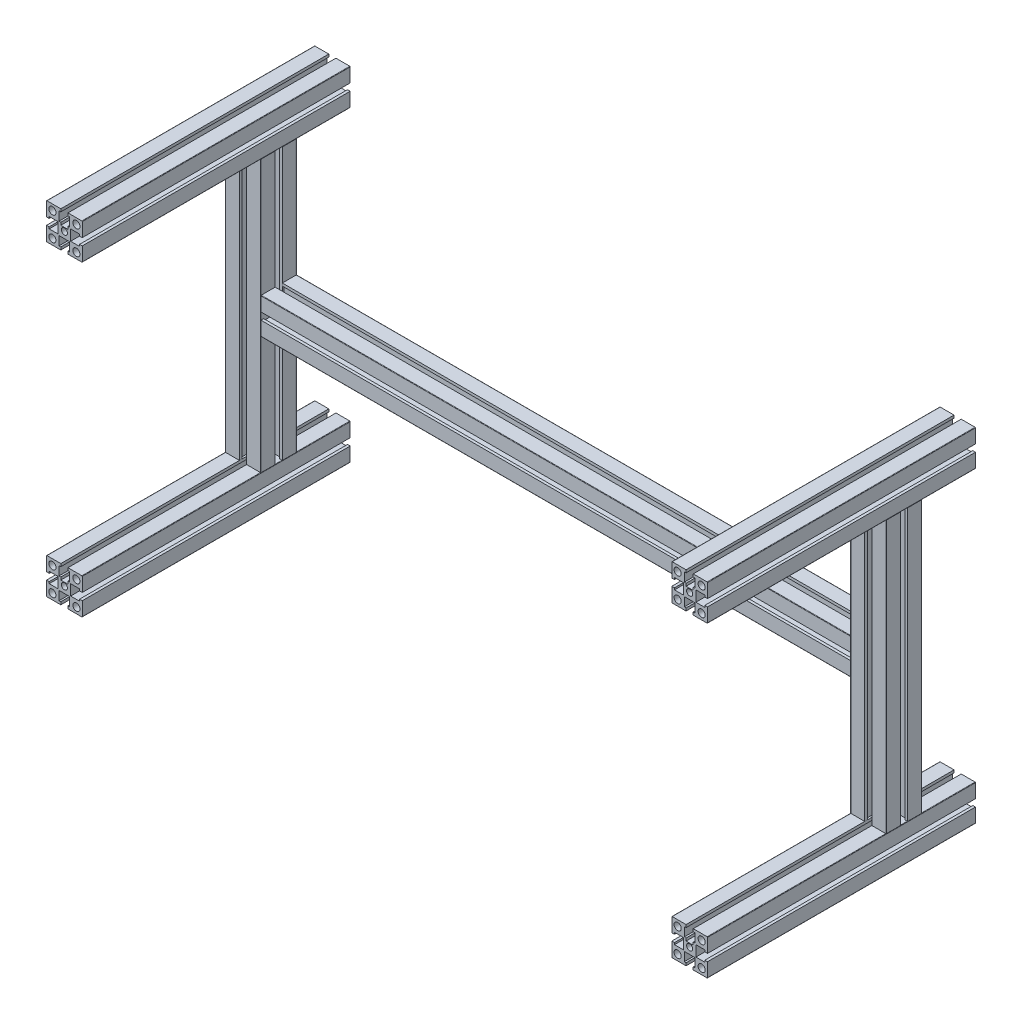
SolidWorks part; units mm, degrees
ref_plane "前视基准面" through (0, 0, 0) normal (0, 0, 1) x (1, 0, 0)
ref_plane "上视基准面" through (0, 0, 0) normal (0, 1, 0) x (1, 0, 0)
ref_plane "右视基准面" through (0, 0, 0) normal (1, 0, 0) x (0, 0, -1)
other "Configuration Table"
sketch3d "3D草图2"
  line L0 (-350, -172, 0) -> (-350, -172, 300)
  line L1 (-350, 172, 0) -> (350, 172, 0) construction
  line L2 (-350, 172, 0) -> (-350, -172, 0) construction
  line L3 (-350, -172, 0) -> (350, -172, 0) construction
  line L4 (350, 172, 0) -> (350, -172, 0) construction
  line L5 (-350, 172, 0) -> (350, -172, 0) construction
  line L6 (-350, -172, 0) -> (350, 172, 0) construction
  line L7 (350, -172, 0) -> (350, -172, 300)
  line L8 (350, 172, 0) -> (350, 172, 300)
  line L9 (-350, 172, 0) -> (-350, 172, 300)
  line L10 (-350, 0, 80) -> (350, 0, 80)
  line L11 (350, -172, 80) -> (-350, -172, 80) construction
  line L12 (350, -172, 80) -> (350, 172, 80)
  line L13 (350, 172, 80) -> (-350, 172, 80) construction
  line L14 (-350, -172, 80) -> (-350, 172, 80)
  point P1 (0, 0, 0)
  dimension "D1" = 700
  dimension "D2" = 344
  dimension "D3" = 80
  dimension "D4" = 300
other "工业铝型材 40 X 40GF X R0.5(1)"
ref_plane "基准面1" through (-350, -172, 0) normal (0, 0, 1) x (1, 0, 0)
sketch "Sketch1" plane through (-350, -172, 0) normal (0, 0, 1) x (1, 0, 0)
  line L0 (0, 0) -> (0, 20) construction
  line L1 (0, 0) -> (-13.435, 13.435) construction
  line L2 (-19.5, 20) -> (-4, 20)
  line L3 (-20, 19.5) -> (-20, 4)
  line L4 (-19.5, -20) -> (-4, -20)
  line L5 (20, 19.5) -> (20, 4)
  line L6 (-4, 7) -> (-4, 4)
  line L7 (-4, 4) -> (4, 4)
  line L8 (4, 4) -> (4, 7)
  line L9 (0, 0) -> (20, 0) construction
  line L10 (4, 7) -> (6, 7)
  line L11 (13.435, 13.435) -> (0, 0) construction
  line L15 (-4, 20) -> (-4, 17)
  line L20 (-6, 17) -> (-4, 17)
  line L21 (-6, 17) -> (-6, 7)
  line L22 (-6, 7) -> (-4, 7)
  line L23 (6, 17) -> (6, 7)
  line L24 (4, 20) -> (4, 17)
  line L25 (4, 20) -> (19.5, 20)
  line L26 (4, 17) -> (6, 17)
  line L31 (17, 6) -> (7, 6)
  line L32 (17, 6) -> (17, 4)
  line L33 (20, 4) -> (17, 4)
  line L34 (7, 6) -> (7, -6)
  line L35 (17, -6) -> (7, -6)
  line L36 (17, -4) -> (17, -6)
  line L37 (20, -4) -> (17, -4)
  line L38 (6, -17) -> (6, -7)
  line L39 (6, -17) -> (4, -17)
  line L40 (4, -20) -> (4, -17)
  line L41 (6, -7) -> (-6, -7)
  line L42 (-6, -17) -> (-6, -7)
  line L43 (-4, -17) -> (-6, -17)
  line L44 (-4, -20) -> (-4, -17)
  line L45 (-17, -6) -> (-7, -6)
  line L46 (-17, -6) -> (-17, -4)
  line L47 (-20, -4) -> (-17, -4)
  line L48 (-7, -6) -> (-7, 6)
  line L49 (-17, 6) -> (-7, 6)
  line L50 (-17, 4) -> (-17, 6)
  line L51 (-20, 4) -> (-17, 4)
  line L52 (4, -20) -> (19.5, -20)
  line L53 (-20, -4) -> (-20, -19.5)
  line L54 (20, -4) -> (20, -19.5)
  circle A0 centre (0, 0) radius 3.4
  circle A1 centre (-13.435, 13.435) radius 4
  circle A2 centre (13.435, 13.435) radius 4
  circle A3 centre (13.435, -13.435) radius 4
  circle A4 centre (-13.435, -13.435) radius 4
  arc A8 (-19.5, 20) -> (-20, 19.5) centre (-19.5, 19.5) ccw
  arc A9 (19.5, 20) -> (20, 19.5) centre (19.5, 19.5) cw
  arc A10 (19.5, -20) -> (20, -19.5) centre (19.5, -19.5) ccw
  arc A11 (-20, -19.5) -> (-19.5, -20) centre (-19.5, -19.5) ccw
  point P10 (20, -20)
  point P13 (20, 20)
  point P14 (-20, 20)
  point P24 (-20, -20)
  point P25 (0, 0)
  dimension "D2" = 3.4
  dimension "D3" = 45
  dimension "D4" = 8
  dimension "D5" = 3
  dimension "D6" = 19
  dimension "D8" = 12
  dimension "D10" = 10
  dimension "D12" = 40
  dimension "D13" = 8
  dimension "D14" = 0.5
equation "\"长\"= 1000mm"
equation "\"宽\"= 300mm"
equation "\"高\"= 500mm"
equation "\"D1@3D草图2\"=\"长\"-300"
equation "\"D2@3D草图2\"=\"宽\"+44"
equation "\"D4@3D草图2\"=\"高\"-200"
